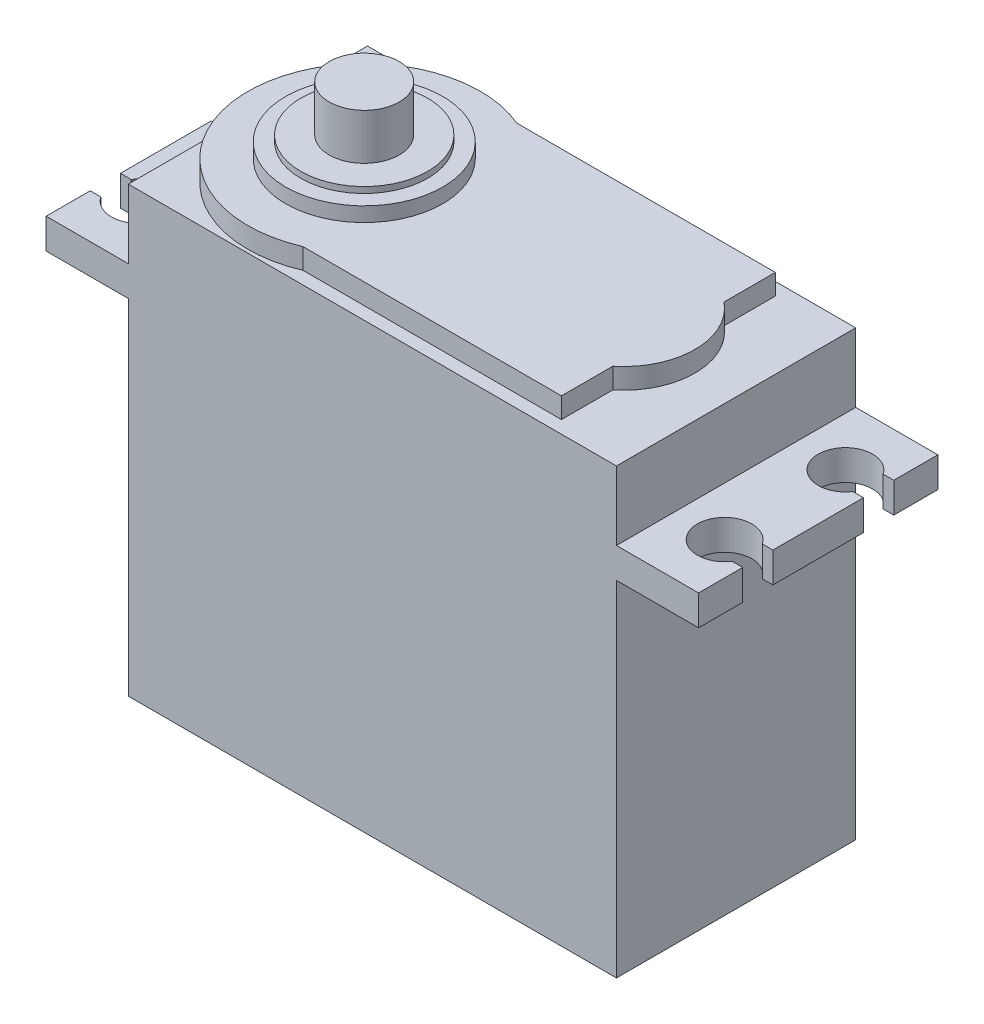
SolidWorks part; units mm, degrees
ref_plane "Front Plane" through (0, 0, 0) normal (0, 0, 1) x (1, 0, 0)
ref_plane "Top Plane" through (0, 0, 0) normal (0, 1, 0) x (1, 0, 0)
ref_plane "Right Plane" through (0, 0, 0) normal (1, 0, 0) x (0, 0, -1)
sketch "Sketch1" plane through (0, 0, 0) normal (0, 1, 0) x (1, 0, 0)
  line L1 (-20.2, -9.9) -> (20.2, -9.9)
  line L2 (-20.2, -9.9) -> (-20.2, 9.9)
  line L3 (-20.2, 9.9) -> (20.2, 9.9)
  line L4 (20.2, -9.9) -> (20.2, 9.9)
  line L5 (0, 9.9) -> (0, -9.9) construction
  line L6 (-20.2, 0) -> (20.2, 0) construction
  point P0 (0, 0)
  dimension "D1" = 40.4
  dimension "D2" = 19.8
extrude "Boss-Extrude1" add sketch "Sketch1" along normal blind 36.7
sketch "Sketch2" plane through (0, 36.7, 0) normal (0, 1, 0) x (1, 0, 0)
  line L0 (-20.2, 0) -> (20.2, 0) construction
  line L1 (-20.2, 9.9) -> (-20.2, -9.9) construction
  line L2 (20.2, -9.9) -> (20.2, 9.9) construction
  line L3 (-20.2, -9.9) -> (20.2, -9.9) construction
  line L4 (-6.7911, -8.85) -> (14.6, -8.85)
  line L6 (-6.7911, 8.85) -> (14.6, 8.85)
  line L7 (14.6, -8.85) -> (14.6, 8.85)
  line L8 (3.9045, 8.85) -> (3.9045, -8.85) construction
  line L9 (-6.7911, 0) -> (14.6, 0) construction
  circle A0 centre (-10.575, 0) radius 9.625
  arc A1 (14.6, -4.6) -> (14.6, 4.6) centre (10.8909, 0) ccw
  point P8 (3.9045, 0)
  point P11 (14.6, -4.6)
  point P13 (14.6, -9.9)
  point P14 (14.6, 4.6)
  point P17 (16.8, 0)
  dimension "D1" = 19.25
  dimension "D6" = 5.9091
  dimension "D2" = 17.7
  dimension "D3" = 5.6
  dimension "D4" = 5.3
  dimension "D5" = 3.4
extrude "Boss-Extrude2" add sketch "Sketch2" along normal blind 1.7 contours A0 | A0 L4 L7 L6 | L7 A1
sketch "Sketch3" plane through (0, 38.4, 0) normal (0, 1, 0) x (1, 0, 0)
  circle A0 centre (-10.575, 0) radius 6.5
  point P0 (-10.575, 0)
  dimension "D1" = 13
extrude "Boss-Extrude3" add sketch "Sketch3" along normal blind 1.2
sketch "Sketch4" plane through (0, 39.6, 0) normal (0, 1, 0) x (1, 0, 0)
  circle A0 centre (-10.575, 0) radius 5.25
  dimension "D1" = 10.5
extrude "Boss-Extrude4" add sketch "Sketch4" along normal blind 0.5
sketch "Sketch5" plane through (0, 40.1, 0) normal (0, 1, 0) x (1, 0, 0)
  circle A0 centre (-10.575, 0) radius 2.9
  dimension "D1" = 5.8
extrude "Boss-Extrude5" add sketch "Sketch5" along normal blind 3.8
sketch "Sketch6" plane through (-20.2, 0, 0) normal (-1, 0, 0) x (0, 0, 1)
  line L0 (-9.9, 31) -> (9.9, 31)
  line L1 (-9.9, 36.7) -> (-9.9, 0) construction
  line L2 (9.9, 36.7) -> (9.9, 0) construction
  line L3 (0, 36.7) -> (-9.625, 36.7) construction
  line L4 (-9.9, 28.5) -> (9.9, 28.5)
  line L5 (-9.9, 31) -> (-9.9, 28.5)
  line L6 (9.9, 31) -> (9.9, 28.5)
  dimension "D1" = 5.7
  dimension "D2" = 2.5
extrude "Boss-Extrude6" add sketch "Sketch6" along normal blind 6.8
sketch "Sketch7" plane through (0, 31, 0) normal (0, 1, 0) x (1, 0, 0)
  line L0 (-27, 0) -> (-20.2, 0) construction
  line L1 (-27, -9.9) -> (-27, 9.9) construction
  line L2 (-20.2, -9.9) -> (-20.2, 9.9) construction
  line L3 (-22, -5) -> (-27, -5) construction
  line L4 (-27, -6.25) -> (-27, -3.75)
  line L5 (-27, -3.75) -> (-26.1208, -3.75)
  line L6 (-27, -6.25) -> (-26.1208, -6.25)
  line L7 (-27, 6.25) -> (-26.1208, 6.25)
  line L8 (-27, 6.25) -> (-27, 3.75)
  line L9 (-27, 3.75) -> (-26.1208, 3.75)
  circle A0 centre (-24.25, -5) radius 2.25
  circle A1 centre (-24.25, 5) radius 2.25
  point P10 (-24.25, 2.75)
  point P11 (-24.25, -2.75)
  point P12 (-22, -5)
  point P15 (-26.5604, -6.25)
  point P18 (-27, -5)
  point P21 (-26.5604, 6.25)
  line M8 (-27, 9.9) -> (-27, -9.9)
  dimension "D1" = 4.5
  dimension "D2" = 5.5
  dimension "D3" = 5
  dimension "D4" = 2.5
extrude "Cut-Extrude1" cut sketch "Sketch7" against normal blind 6.8 contours A1 | L9 A1 L7 M8 | A0 | A0 L5 L6 M8
mirror "Mirror1" about plane through (0, 0, 0) normal (1, 0, 0) of "Boss-Extrude6", "Cut-Extrude1"
sketch "Sketch8" plane through (-20.2, 0, 0) normal (-1, 0, 0) x (0, 0, 1)
  line L0 (-9.9, 0) -> (9.9, 0) construction
  line L1 (0, 0) -> (0, 3.7) construction
  line L2 (-3.75, 3.7) -> (3.75, 3.7) construction
  line L3 (-3.75, 3.7) -> (3.75, 3.7)
  line L4 (-3.75, 3.7) -> (-3.75, 8.7)
  line L5 (3.75, 3.7) -> (3.75, 8.7)
  line L6 (-3.75, 8.7) -> (3.75, 8.7)
  point P0 (0, 0)
  point P8 (0, 3.7)
  dimension "D1" = 3.7
  dimension "D2" = 7.5
  dimension "D3" = 5
extrude "Boss-Extrude7" add sketch "Sketch8" along normal blind 6
